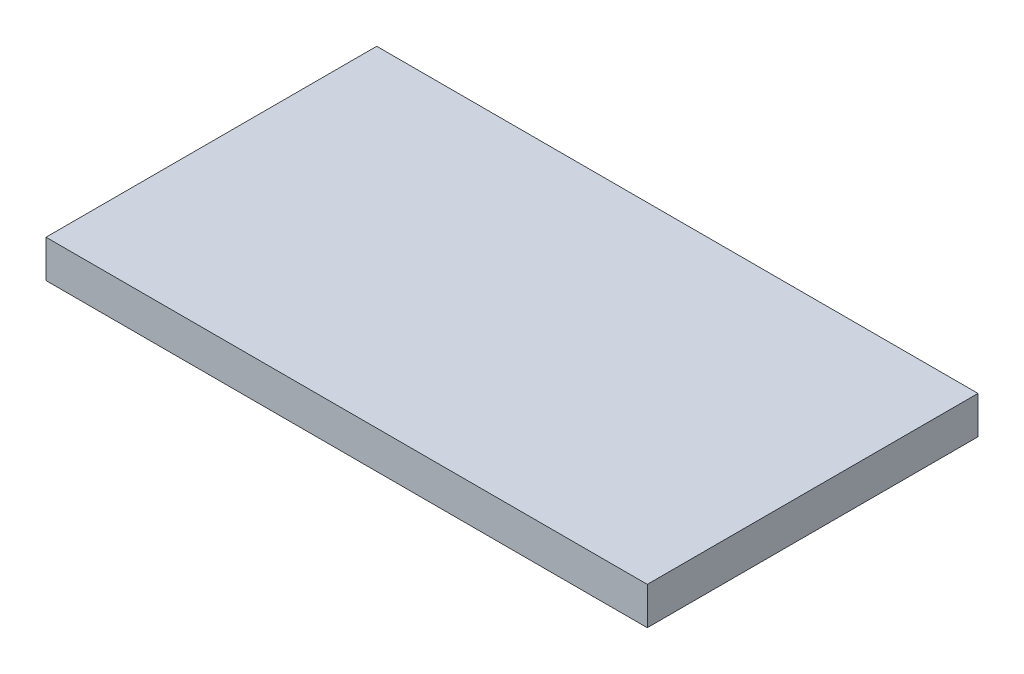
SolidWorks part; units mm, degrees
ref_plane "Front Plane" through (0, 0, 0) normal (0, 0, 1) x (1, 0, 0)
ref_plane "Top Plane" through (0, 0, 0) normal (0, 1, 0) x (1, 0, 0)
ref_plane "Right Plane" through (0, 0, 0) normal (1, 0, 0) x (0, 0, -1)
sketch "Sketch1" plane through (0, 0, 0) normal (0, 1, 0) x (1, 0, 0)
  line L1 (-80, 44) -> (80, 44)
  line L2 (-80, 44) -> (-80, -44)
  line L3 (-80, -44) -> (80, -44)
  line L4 (80, 44) -> (80, -44)
  line L5 (-80, 44) -> (80, -44) construction
  line L6 (-80, -44) -> (80, 44) construction
  point P0 (0, 0)
  dimension "D1" = 88
  dimension "D2" = 160
extrude "Boss-Extrude1" add sketch "Sketch1" along normal blind 10
